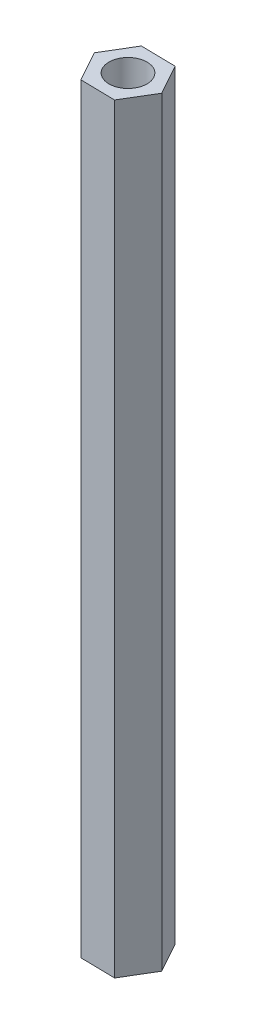
SolidWorks part; units mm, degrees
ref_plane "Front Plane" through (0, 0, 0) normal (0, 0, 1) x (1, 0, 0)
ref_plane "Top Plane" through (0, 0, 0) normal (0, 1, 0) x (1, 0, 0)
ref_plane "Right Plane" through (0, 0, 0) normal (1, 0, 0) x (0, 0, -1)
sketch "Sketch1" plane through (0, 0, 0) normal (0, 1, 0) x (1, 0, 0)
  line L1 (-1.3134, 2.3745) -> (-2.7131, 0.0498)
  line L2 (-2.7131, 0.0498) -> (-1.3997, -2.3247)
  line L3 (-1.3997, -2.3247) -> (1.3134, -2.3745)
  line L4 (1.3134, -2.3745) -> (2.7131, -0.0498)
  line L5 (2.7131, -0.0498) -> (1.3997, 2.3247)
  line L6 (1.3997, 2.3247) -> (-1.3134, 2.3745)
  circle A0 centre (0, 0) radius 2.35 construction
  circle A1 centre (0, 0) radius 1.5
  dimension "D2" = 3
  dimension "D1" = 4.7
extrude "Boss-Extrude1" add sketch "Sketch1" along normal blind 60
